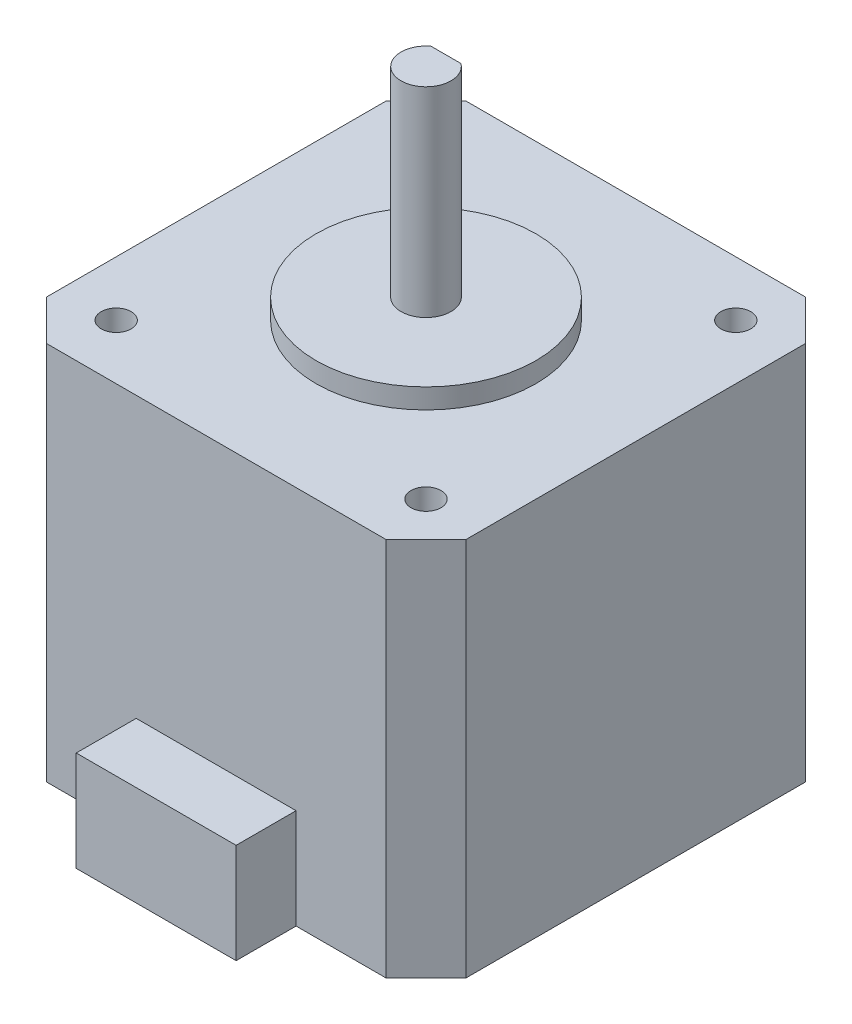
SolidWorks part; units mm, degrees
ref_plane "前视基准面" through (0, 0, 0) normal (0, 0, 1) x (1, 0, 0)
ref_plane "上视基准面" through (0, 0, 0) normal (0, 1, 0) x (1, 0, 0)
ref_plane "右视基准面" through (0, 0, 0) normal (1, 0, 0) x (0, 0, -1)
sketch "草图1" plane through (0, 0, 0) normal (0, 1, 0) x (1, 0, 0)
  line L1 (-21, -21) -> (21, -21)
  line L2 (-21, -21) -> (-21, 21)
  line L3 (-21, 21) -> (21, 21)
  line L4 (21, -21) -> (21, 21)
  line L5 (-21, -21) -> (21, 21) construction
  line L6 (-21, 21) -> (21, -21) construction
  point P0 (0, 0)
  dimension "D1" = 42
extrude "凸台-拉伸1" add sketch "草图1" along normal blind 38
sketch "草图2" plane through (0, 38, 0) normal (0, 1, 0) x (1, 0, 0)
  circle A0 centre (0, 0) radius 11
  dimension "D1" = 22
extrude "凸台-拉伸2" add sketch "草图2" along normal blind 2
sketch "草图3" plane through (0, 40, 0) normal (0, 1, 0) x (1, 0, 0)
  circle A0 centre (0, 0) radius 2.5
  dimension "D1" = 5
extrude "凸台-拉伸3" add sketch "草图3" along normal blind 20
sketch "草图4" plane through (0, 60, 0) normal (0, 1, 0) x (1, 0, 0)
  line L0 (-1.5, 2) -> (1.5, 2)
  circle A0 centre (0, 0) radius 2.5 construction
  arc A1 (1.5, 2) -> (-1.5, 2) centre (0, 0) ccw
  dimension "D1" = 2
extrude "切除-拉伸1" cut sketch "草图4" against normal blind 15
sketch "草图5" plane through (0, 38, 0) normal (0, 1, 0) x (1, 0, 0)
  line L0 (-1000, 0) -> (49000, 0) construction
  line L1 (0, -1000) -> (0, 49000) construction
  circle A0 centre (15.5, 15.5) radius 1.5
  dimension "D1" = 3
  dimension "D2" = 31
  dimension "D3" = 31
extrude "切除-拉伸2" cut sketch "草图5" against normal blind 4.5
pattern_circular "阵列(圆周)1" count 4 over 360 about axis through (0, 0, 0) along (0, 1, 0) of "切除-拉伸2"
sketch "草图6" plane through (0, 0, 0) normal (0, -1, 0) x (1, 0, 0)
  line L0 (0, -1000) -> (0, 49000) construction
  line L1 (-21, 21) -> (21, 21) construction
  line L2 (-8, 21) -> (8, 21)
  line L3 (-8, 21) -> (-8, 27)
  line L4 (-8, 27) -> (8, 27)
  line L5 (8, 21) -> (8, 27)
  dimension "D1" = 6
  dimension "D2" = 16
extrude "凸台-拉伸4" add sketch "草图6" against normal blind 10
chamfer "倒角1" distance 4 angle 45 4 edges at (-21, 19, 21) (-21, 19, -21) (21, 19, -21) (21, 19, 21)
